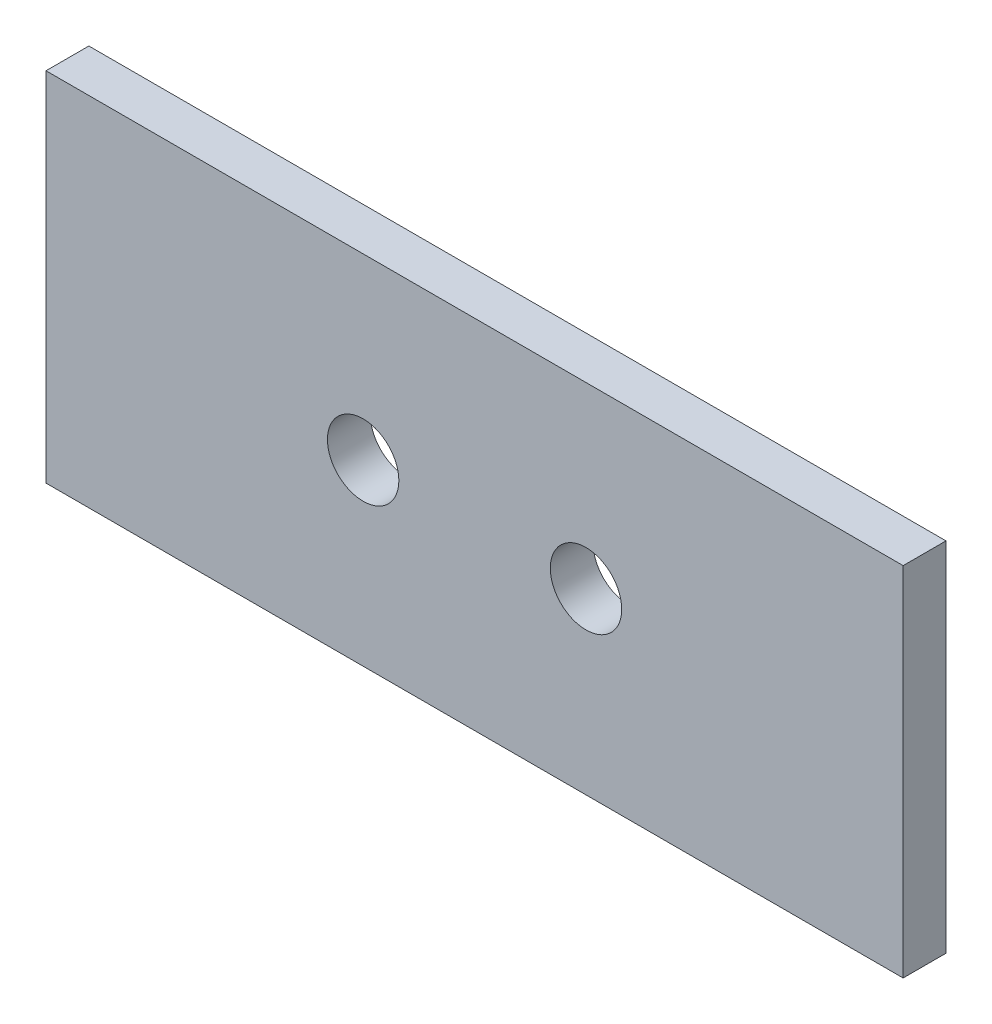
SolidWorks part; units mm, degrees
ref_plane "前视" through (0, 0, 0) normal (0, 0, 1) x (1, 0, 0)
ref_plane "上视" through (0, 0, 0) normal (0, 1, 0) x (1, 0, 0)
ref_plane "右视" through (0, 0, 0) normal (1, 0, 0) x (0, 0, -1)
sketch "Sketch1" plane through (0, 0, 0) normal (0, 0, 1) x (1, 0, 0)
  line L0 (0, 81.2569) -> (0, -74.9762) construction
  line L1 (-30, 12.5) -> (30, 12.5)
  line L2 (-30, 12.5) -> (-30, -12.5)
  line L3 (-30, -12.5) -> (30, -12.5)
  line L4 (30, 12.5) -> (30, -12.5)
  line L5 (-98.5289, 0) -> (102.8469, 0) construction
  dimension "D1" = 25
  dimension "D2" = 60
extrude "Extrude1" add sketch "Sketch1" along normal mid plane 3
sketch "Sketch2" plane through (0, 0, 1.5) normal (0, 0, 1) x (1, 0, 0)
  line L0 (-33.438, 0) -> (34.9366, 0) construction
  circle A0 centre (-7.8, 0) radius 2.5
  circle A1 centre (7.8, 0) radius 2.5
  dimension "D1" = 5
  dimension "D3" = 5
  dimension "D2" = 15.6
extrude "Cut-Extrude1" cut sketch "Sketch2" against normal blind 10
